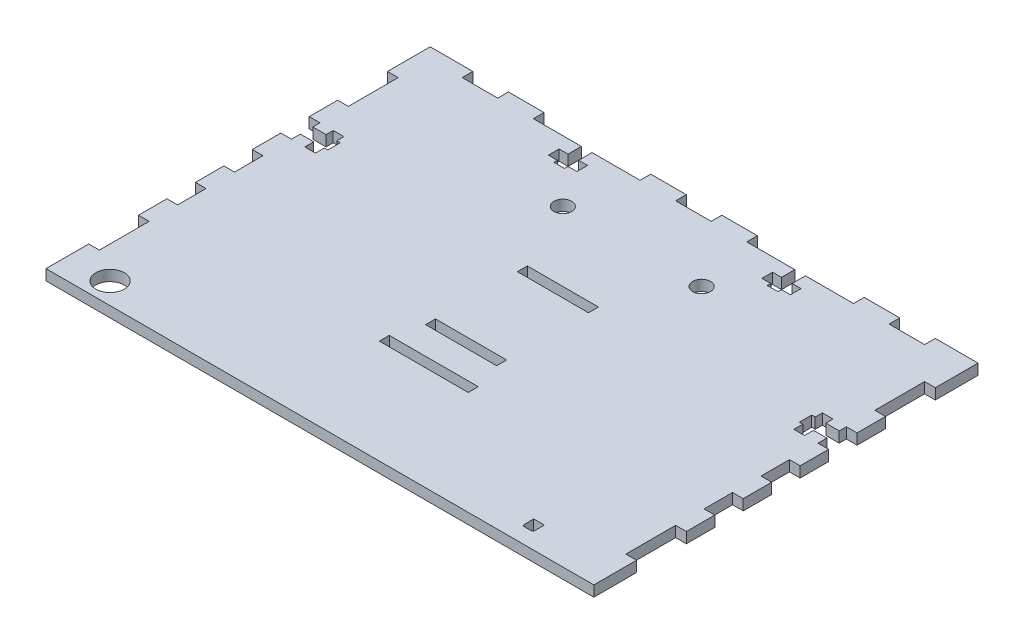
SolidWorks part; units mm, degrees
material "Balsa"
ref_plane "Alzado" through (0, 0, 0) normal (0, 0, 1) x (1, 0, 0)
ref_plane "Planta" through (0, 0, 0) normal (0, 1, 0) x (1, 0, 0)
ref_plane "Vista lateral" through (0, 0, 0) normal (1, 0, 0) x (0, 0, -1)
sketch "Croquis1" plane through (0, 0, 0) normal (0, 1, 0) x (1, 0, 0)
  line L0 (-77, 0) -> (-74, 0) construction
  line L1 (-77, -54) -> (77, -54)
  line L2 (-77, -54) -> (-77, 54)
  line L3 (-77, 54) -> (77, 54)
  line L4 (77, -54) -> (77, 54)
  line L5 (-77, -54) -> (77, 54) construction
  line L6 (-77, 54) -> (77, -54) construction
  line L7 (0, -54) -> (0, 54) construction
  line L8 (-74, 54) -> (-74, -54) construction
  line L9 (-77, -42) -> (-74, -42)
  line L10 (-77, 4) -> (-74, 4)
  line L11 (-77, 4) -> (-77, -4)
  line L12 (-77, -4) -> (-74, -4)
  line L13 (-74, 4) -> (-74, -4)
  line L14 (-77, 12) -> (-74, 12)
  line L15 (-77, 12) -> (-77, 20)
  line L16 (-77, 20) -> (-74, 20)
  line L17 (-74, 12) -> (-74, 20)
  line L22 (-77, 28) -> (-74, 28)
  line L23 (-77, 28) -> (-77, 42)
  line L24 (-77, 42) -> (-74, 42)
  line L25 (-74, 28) -> (-74, 42)
  line L26 (-74, -28) -> (-74, -42)
  line L27 (-77, -28) -> (-74, -28)
  line L28 (-77, -28) -> (-77, -42)
  line L29 (-77, -20) -> (-74, -20)
  line L30 (-74, -12) -> (-74, -20)
  line L31 (-77, -12) -> (-74, -12)
  line L32 (-77, -12) -> (-77, -20)
  line L33 (77, 42) -> (74, 42)
  line L34 (74, 28) -> (74, 42)
  line L35 (77, 28) -> (74, 28)
  line L36 (77, 28) -> (77, 42)
  line L37 (77, -28) -> (77, -42)
  line L38 (77, -28) -> (74, -28)
  line L39 (74, -28) -> (74, -42)
  line L40 (77, -42) -> (74, -42)
  line L41 (77, -12) -> (77, -20)
  line L42 (77, -12) -> (74, -12)
  line L43 (74, -12) -> (74, -20)
  line L44 (77, -20) -> (74, -20)
  line L45 (77, 20) -> (74, 20)
  line L46 (74, 12) -> (74, 20)
  line L47 (77, 12) -> (74, 12)
  line L48 (77, 12) -> (77, 20)
  line L49 (77, -4) -> (74, -4)
  line L50 (74, 4) -> (74, -4)
  line L51 (77, 4) -> (74, 4)
  line L52 (77, 4) -> (77, -4)
  line L53 (-77, 51) -> (77, 51) construction
  line L54 (-55, 51) -> (-65, 51)
  line L55 (-5, 54) -> (5, 54)
  line L56 (-5, 54) -> (-5, 51)
  line L57 (-5, 51) -> (5, 51)
  line L58 (5, 54) -> (5, 51)
  line L59 (15, 54) -> (45, 54)
  line L60 (15, 54) -> (15, 51)
  line L61 (15, 51) -> (45, 51)
  line L62 (45, 54) -> (45, 51)
  line L63 (55, 54) -> (65, 54)
  line L64 (55, 54) -> (55, 51)
  line L65 (55, 51) -> (65, 51)
  line L66 (65, 54) -> (65, 51)
  line L67 (-65, 54) -> (-65, 51)
  line L68 (-55, 54) -> (-65, 54)
  line L69 (-55, 54) -> (-55, 51)
  line L70 (-15, 51) -> (-45, 51)
  line L71 (-45, 54) -> (-45, 51)
  line L72 (-15, 54) -> (-45, 54)
  line L73 (-15, 54) -> (-15, 51)
  line L74 (-77, -48) -> (77, -48) construction
  line L75 (-30, 51) -> (-30, 10.4132) construction
  line L76 (53, -49.6) -> (55, -49.6)
  line L77 (52.5, -49.1) -> (52.5, -46.4)
  line L78 (52.5, -46.4) -> (55.5, -46.4)
  line L79 (55.5, -49.1) -> (55.5, -46.4)
  line L80 (52.5, -49.6) -> (55.5, -46.4) construction
  line L81 (52.5, -46.4) -> (55.5, -49.6) construction
  line L83 (-74, 1.5) -> (-74, -1.5)
  line L90 (-31.5, 51) -> (-28.5, 51)
  line L91 (-31.5, 51) -> (-31.5, 43.27)
  line L92 (-31.5, 43.27) -> (-28.5, 43.27)
  line L93 (-28.5, 51) -> (-28.5, 43.27)
  line L94 (-34, 47.25) -> (-26, 47.25)
  line L95 (-34, 47.25) -> (-34, 44.25)
  line L96 (-34, 44.25) -> (-26, 44.25)
  line L97 (-26, 47.25) -> (-26, 44.25)
  line L98 (31.5, 43.27) -> (28.5, 43.27)
  line L99 (28.5, 51) -> (28.5, 43.27)
  line L100 (31.5, 51) -> (28.5, 51)
  line L101 (31.5, 51) -> (31.5, 43.27)
  line L102 (34, 44.25) -> (26, 44.25)
  line L103 (26, 47.25) -> (26, 44.25)
  line L104 (34, 47.25) -> (26, 47.25)
  line L105 (34, 47.25) -> (34, 44.25)
  line L109 (74, 1.5) -> (74, -1.5)
  line L114 (-74, 16) -> (74, 16) construction
  line L115 (74, 17.9921) -> (66.27, 17.9921)
  line L116 (-74, 14.4979) -> (-66.27, 14.4979)
  line L117 (-74, 14.4979) -> (-74, 17.9921)
  line L118 (-74, 17.9921) -> (-66.27, 17.9921)
  line L119 (-66.27, 14.4979) -> (-66.27, 17.9921)
  line L120 (-70.25, 12) -> (-67.25, 12)
  line L121 (-70.25, 12) -> (-70.25, 20)
  line L122 (-70.25, 20) -> (-67.25, 20)
  line L123 (-67.25, 12) -> (-67.25, 20)
  line L124 (66.27, 14.4979) -> (66.27, 17.9921)
  line L125 (74, 0) -> (77, 0) construction
  line L126 (74, 14.4979) -> (66.27, 14.4979)
  line L127 (74, 14.4979) -> (74, 17.9921)
  line L128 (70.25, 20) -> (67.25, 20)
  line L129 (67.25, 12) -> (67.25, 20)
  line L130 (70.25, 12) -> (67.25, 12)
  line L131 (70.25, 12) -> (70.25, 20)
  circle A0 centre (-65, -48) radius 4
  arc A1 (55.5, -49.1) -> (55, -49.6) centre (55, -49.1) cw
  arc A2 (53, -49.6) -> (52.5, -49.1) centre (53, -49.1) cw
  point P0 (0, 0)
  point P78 (54, -48)
  point P123 (-75.5, 4)
  dimension "D17" = 8
  dimension "D22" = 0.5
  dimension "D1" = 108
  dimension "D2" = 154
  dimension "D3" = 3
  dimension "D4" = 4
  dimension "D5" = 3
  dimension "D6" = 8
  dimension "D7" = 8
  dimension "D8" = 8
  dimension "D9" = 14
  dimension "D10" = 3
  dimension "D11" = 5
  dimension "D12" = 10
  dimension "D13" = 10
  dimension "D14" = 30
  dimension "D15" = 10
  dimension "D16" = 10
  dimension "D18" = 6
  dimension "D19" = 23
  dimension "D20" = 3.2
  dimension "D21" = 3
  dimension "D23" = 12
  dimension "D31" = 3
  dimension "D32" = 8
  dimension "D33" = 1.5
  dimension "D34" = 4
  dimension "D35" = 0.98
  dimension "D36" = 7.73
  dimension "D37" = 8
  dimension "D38" = 7.73
  dimension "D39" = 3.4942
  dimension "D40" = 1.5021
  dimension "D41" = 0.98
  dimension "D42" = 8
  dimension "D43" = 4
  dimension "D44" = 3
extrude "Saliente-Extruir1" add sketch "Croquis1" along normal mid plane 3
sketch "Croquis3" plane through (0, 1.5, 0) normal (0, 1, 0) x (1, 0, 0)
  line L0 (-15, 54) -> (-5, 54) construction
  line L1 (-10, 14.3) -> (10, 14.3)
  line L2 (-10, 14.3) -> (-10, 11.5)
  line L3 (-10, 11.5) -> (10, 11.5)
  line L4 (10, 14.3) -> (10, 11.5)
  line L5 (-10, -11.5) -> (10, -11.5)
  line L6 (-10, -11.5) -> (-10, -14.3)
  line L7 (-10, -14.3) -> (10, -14.3)
  line L8 (10, -11.5) -> (10, -14.3)
  line L9 (-12.5, -22) -> (12.5, -22)
  line L10 (-12.5, -22) -> (-12.5, -24.8)
  line L11 (-12.5, -24.8) -> (12.5, -24.8)
  line L12 (12.5, -22) -> (12.5, -24.8)
  line L13 (5, 54) -> (15, 54) construction
  line L14 (0, -11.5) -> (0, 11.5) construction
  line L15 (0, 0) -> (5.4909, 0) construction
  circle A0 centre (-19.5, 33.79) radius 2.5
  circle A1 centre (19.5, 33.79) radius 2.5
  dimension "D1" = 5
  dimension "D2" = 5
  dimension "D3" = 39
  dimension "D4" = 19.5
  dimension "D5" = 20.21
  dimension "D6" = 2.8
  dimension "D7" = 20
  dimension "D8" = 10
  dimension "D9" = 2.8
  dimension "D10" = 20
  dimension "D11" = 10
  dimension "D12" = 23
  dimension "D13" = 11.5
  dimension "D14" = 25
  dimension "D15" = 2.8
  dimension "D16" = 12.5
  dimension "D17" = 7.7
  dimension "D18" = 20.21
  dimension "D19" = 54
extrude "Cortar-Extruir2" cut sketch "Croquis3" against normal blind 3
